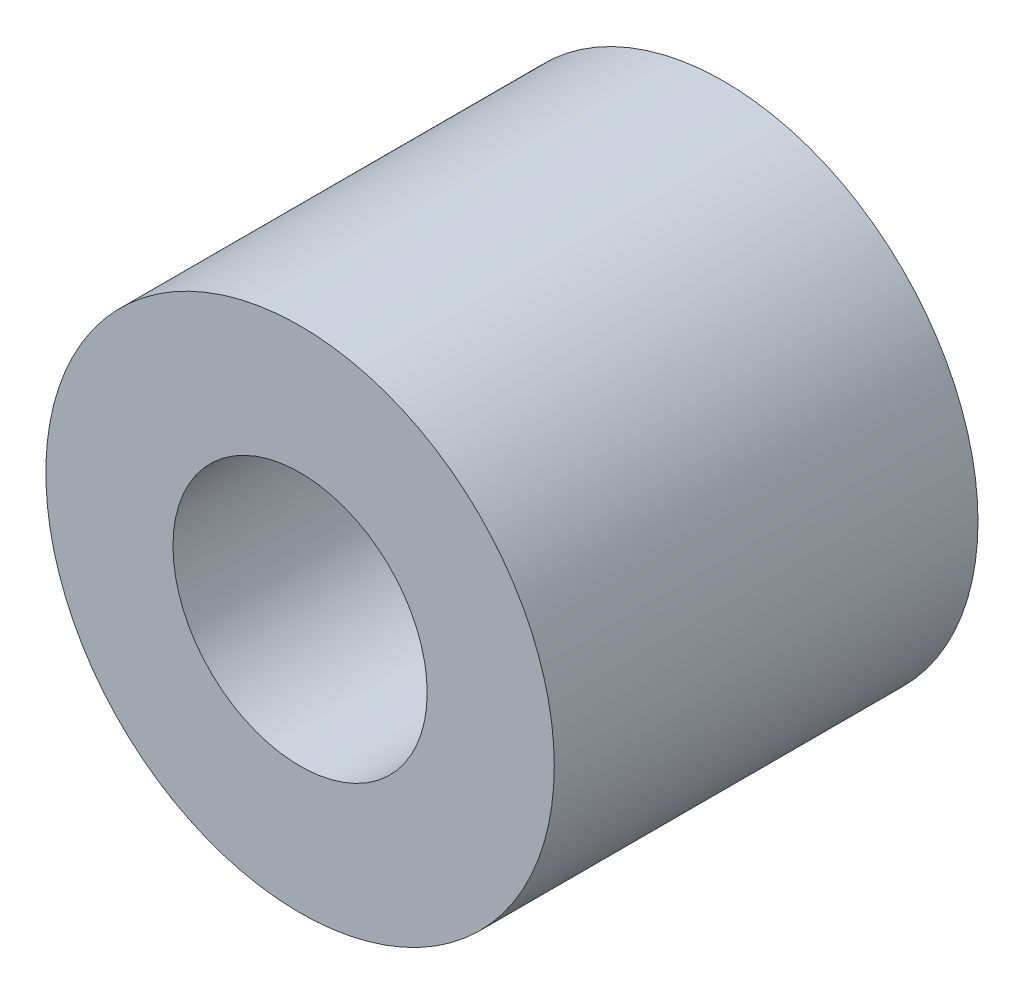
SolidWorks part; units mm, degrees
ref_plane "正面" through (0, 0, 0) normal (0, 0, 1) x (1, 0, 0)
ref_plane "平面" through (0, 0, 0) normal (0, 1, 0) x (1, 0, 0)
ref_plane "右側面" through (0, 0, 0) normal (1, 0, 0) x (0, 0, -1)
sketch "ｽｹｯﾁ1" plane through (0, 0, 0) normal (0, 0, 1) x (1, 0, 0)
  circle A0 centre (0, 0) radius 3
  circle A1 centre (0, 0) radius 1.5
  dimension "D1" = 3
  dimension "D2" = 6
extrude "ﾎﾞｽ - 押し出し1" add sketch "ｽｹｯﾁ1" along normal blind 5
